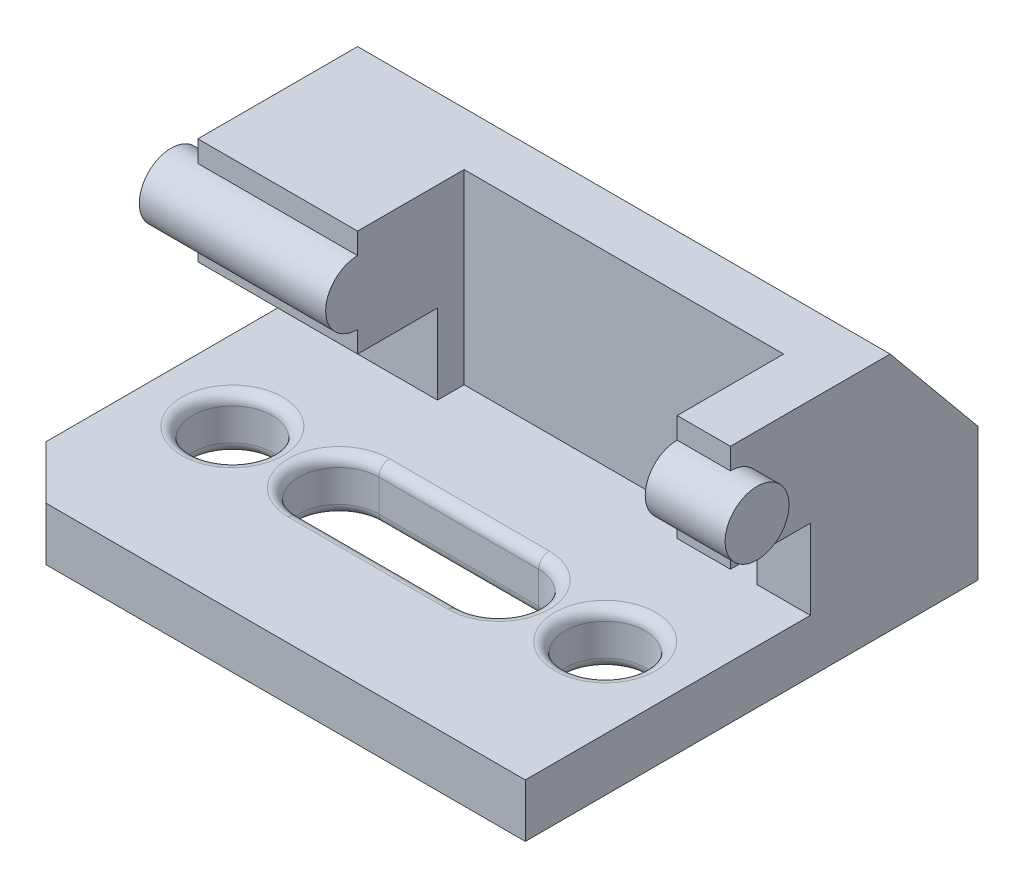
SolidWorks part; units mm, degrees
material "1060 Alloy"
ref_plane "Front Plane" through (0, 0, 0) normal (0, 0, 1) x (1, 0, 0)
ref_plane "Top Plane" through (0, 0, 0) normal (0, 1, 0) x (1, 0, 0)
ref_plane "Right Plane" through (0, 0, 0) normal (1, 0, 0) x (0, 0, -1)
sketch "Sketch1" plane through (0, 0, 0) normal (0, 1, 0) x (1, 0, 0)
  line L0 (-50, -32.5) -> (-40, -42.5)
  line L1 (50, -42.5) -> (-40, -42.5)
  line L2 (50, -42.5) -> (50, 42.5)
  line L3 (50, 42.5) -> (-50, 42.5)
  line L4 (-50, -32.5) -> (-50, 42.5)
  line L5 (50, -42.5) -> (-50, 42.5) construction
  line L6 (50, 42.5) -> (-44.5946, -37.9054) construction
  line L7 (0, 0) -> (0, 42.5) construction
  point P0 (0, 0)
  dimension "D1" = 100
  dimension "D2" = 85
  dimension "D3" = 45
  dimension "D4" = 10
extrude "Boss-Extrude1" add sketch "Sketch1" along normal blind 10
sketch "Sketch2" plane through (0, 10, 0) normal (0, 1, 0) x (1, 0, 0)
  line L0 (-40, -42.5) -> (50, -42.5) construction
  line L1 (50, -42.5) -> (50, 42.5) construction
  line L2 (-50, 42.5) -> (-50, -32.5) construction
  line L3 (0, 42.5) -> (0, -42.5) construction
  line L10 (15, -5) -> (-15, -5)
  line L11 (50, 42.5) -> (-50, 42.5) construction
  line L12 (15, -20) -> (-15, -20)
  circle A0 centre (-35, -12.5) radius 7.5
  circle A1 centre (35, -12.5) radius 7.5
  arc A4 (15, -20) -> (15, -5) centre (15, -12.5) ccw
  arc A5 (-15, -20) -> (-15, -5) centre (-15, -12.5) cw
  point P23 (0, -20)
  point P25 (0, -5)
  dimension "D4" = 15
  dimension "D6" = 15
  dimension "D5" = 15
  dimension "D1" = 30
  dimension "D2" = 15
  dimension "D3" = 15
extrude "Cut-Extrude1" cut sketch "Sketch2" against normal blind 10
sketch "Sketch3" plane through (-50, 0, 0) normal (-1, 0, 0) x (0, 0, 1)
  line L0 (-42.5, 10) -> (-42.5, 25)
  line L1 (-42.5, 25) -> (-26.0133, 45)
  line L2 (-26.0133, 45) -> (3.9867, 45)
  line L3 (3.9867, 45) -> (3.9867, 25)
  line L4 (3.9867, 25) -> (-11.0133, 25)
  line L5 (-11.0133, 25) -> (-11.0133, 10)
  line L6 (-42.5, 10) -> (32.5, 10) construction
  line L7 (-42.5, 10) -> (-11.0133, 10)
  dimension "D1" = 15
  dimension "D2" = 20
  dimension "D3" = 30
  dimension "D4" = 20
  dimension "D5" = 15
  dimension "D6" = 39.5
extrude "Boss-Extrude2" add sketch "Sketch3" against normal up to surface (100 mm away) up to face at (50, 5, 0)
sketch "Sketch4" plane through (-50, 0, 0) normal (-1, 0, 0) x (0, 0, 1)
  line L0 (3.9867, 25) -> (3.9867, 45) construction
  circle A0 centre (3.9867, 35) radius 6
  dimension "D1" = 12
extrude "Boss-Extrude3" add sketch "Sketch4" against normal blind 110 from offset 5
sketch "Sketch5" plane through (0, 30.9745, -37.575) normal (0, 0.6361, -0.7716) x (1, 0, 0)
  line L0 (-50, -18.1766) -> (-50, 7.7427) construction
  circle A0 centre (-50, -5.217) radius 7.5
  dimension "D1" = 15
extrude "Cut-Extrude2" cut sketch "Sketch5" against normal blind 20
sketch "Sketch6" plane through (0, 45, 0) normal (0, 1, 0) x (1, 0, 0)
  line L0 (50, 2.9218) -> (40, 2.9218) construction
  line L1 (50, 26.0133) -> (50, -3.9867) construction
  line L2 (40, 2.9218) -> (-20, 2.9218) construction
  line L3 (40, -20.1833) -> (40, 16.0133)
  line L4 (40, 16.0133) -> (-20, 16.0133)
  line L5 (-20, 16.0133) -> (-20, -20.1833)
  line L6 (50, 26.0133) -> (-50, 26.0133) construction
  line L7 (-20, -20.1833) -> (40, -20.1833)
  point P11 (10, 16.0133)
  dimension "D1" = 10
  dimension "D2" = 60
  dimension "D3" = 10
extrude "Cut-Extrude3" cut sketch "Sketch6" against normal up to surface (35 mm away) up to face at (-35, 10, 20)
fillet "Fillet1" radius 2 12 edges at (35, 0, 20) (-35, 0, 20) (-35, 10, 20) (35, 10, 20) (0, 0, 5) (22.5, 0, 12.5) (0, 0, 20) (0, 10, 5) (22.5, 10, 12.5) (0, 10, 20) (-22.5, 0, 12.5) (-22.5, 10, 12.5)
